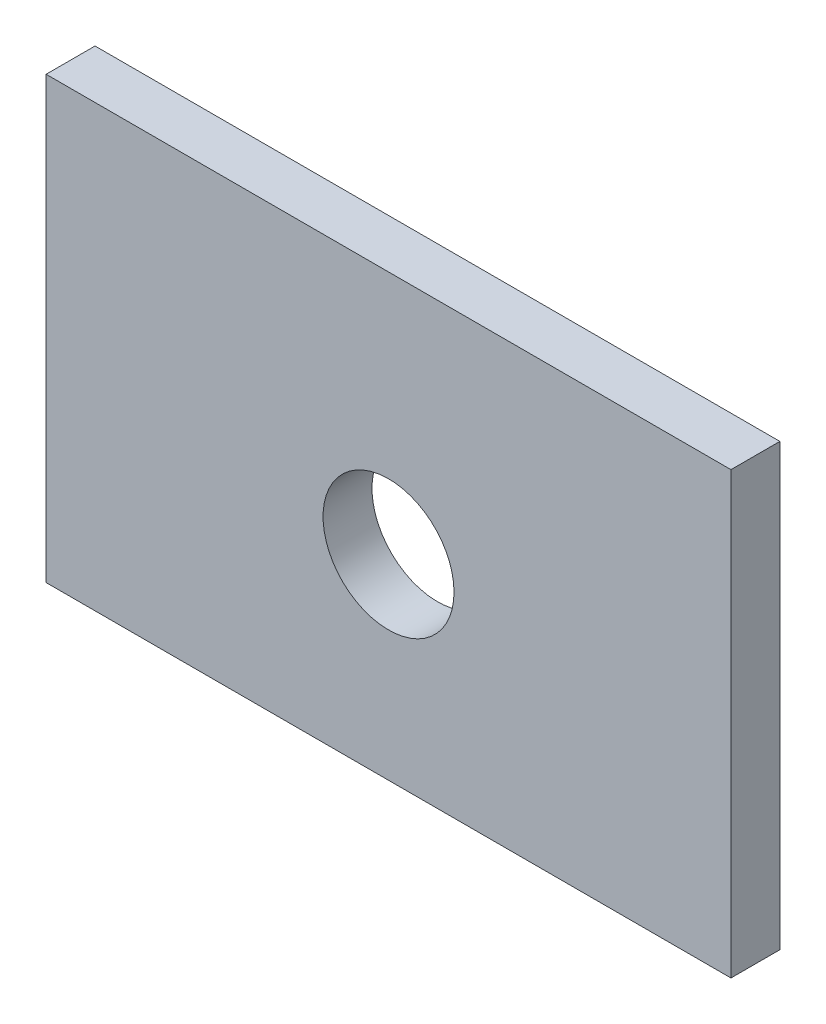
SolidWorks part; units mm, degrees
ref_plane "Front Plane" through (0, 0, 0) normal (0, 0, 1) x (1, 0, 0)
ref_plane "Top Plane" through (0, 0, 0) normal (0, 1, 0) x (1, 0, 0)
ref_plane "Right Plane" through (0, 0, 0) normal (1, 0, 0) x (0, 0, -1)
sketch "Sketch1" plane through (0, 0, 0) normal (0, 0, 1) x (1, 0, 0)
  line L1 (-44.45, 28.575) -> (44.45, 28.575)
  line L2 (-44.45, 28.575) -> (-44.45, -28.575)
  line L3 (-44.45, -28.575) -> (44.45, -28.575)
  line L4 (44.45, 28.575) -> (44.45, -28.575)
  line L5 (-44.45, 28.575) -> (44.45, -28.575) construction
  line L6 (-44.45, -28.575) -> (44.45, 28.575) construction
  point P0 (0, 0)
  dimension "D1" = 57.15
  dimension "D2" = 88.9
extrude "Boss-Extrude1" add sketch "Sketch1" along normal blind 6.35
sketch "Sketch2" plane through (0, 0, 6.35) normal (0, 0, 1) x (1, 0, 0)
  line L0 (44.45, -28.575) -> (-44.45, -28.575) construction
  circle A0 centre (0, -3.175) radius 8.5
  dimension "D1" = 25.4
extrude "Cut-Extrude1" cut sketch "Sketch2" against normal up to next
